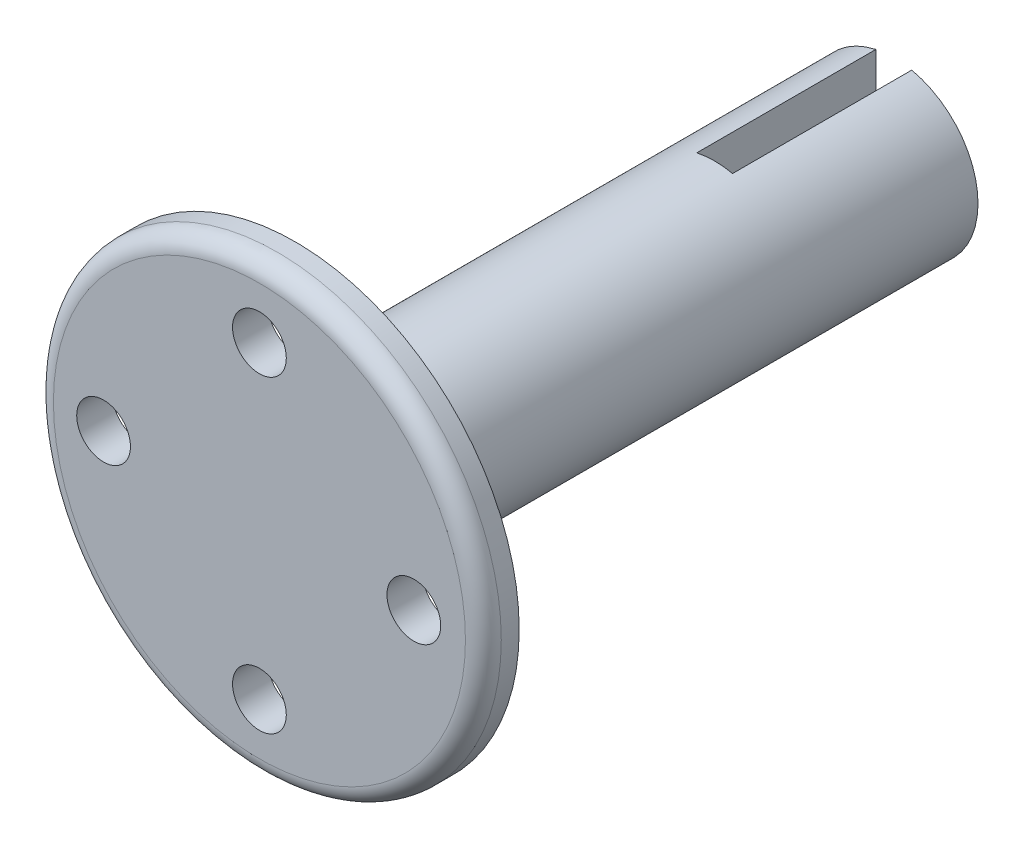
SolidWorks part; units mm, degrees
ref_plane "Alzado" through (0, 0, 0) normal (0, 0, 1) x (1, 0, 0)
ref_plane "Planta" through (0, 0, 0) normal (0, 1, 0) x (1, 0, 0)
ref_plane "Vista lateral" through (0, 0, 0) normal (1, 0, 0) x (0, 0, -1)
sketch "Croquis1" plane through (0, 0, 0) normal (0, 0, 1) x (1, 0, 0)
  circle A0 centre (0, 0) radius 12.5
  dimension "D1" = 25
extrude "Saliente-Extruir1" add sketch "Croquis1" along normal blind 2
fillet "Redondeo2" radius 1 1 edges at (12.5, 0, 2)
sketch "Croquis2" plane through (0, 0, 0) normal (0, 0, -1) x (-1, 0, 0)
  circle A0 centre (0, 0) radius 5
  dimension "D1" = 10
extrude "Saliente-Extruir2" add sketch "Croquis2" along normal blind 33.41
sketch "Croquis3" plane through (0, 0, 0) normal (0, 0, -1) x (-1, 0, 0)
  line L0 (0, 8.62) -> (0, -0.2266) construction
  line L1 (0, -0.2266) -> (0, -8.62) construction
  line L2 (8.7, 0) -> (0, 0) construction
  line L3 (0, 0) -> (-8.62, 0) construction
  circle A0 centre (0, 8.62) radius 1.5
  circle A1 centre (-8.62, 0) radius 1.5
  circle A2 centre (8.7, 0) radius 1.5
  circle A3 centre (0, -8.62) radius 1.5
  circle A4 centre (0, 0) radius 5 construction
  circle A5 centre (0, 0) radius 5 construction
  dimension "D1" = 3
  dimension "D2" = 3
  dimension "D3" = 3
  dimension "D4" = 3
  dimension "D5" = 2.12
  dimension "D6" = 2.12
  dimension "D7" = 2.12
  dimension "D8" = 2.2
extrude "Cortar-Extruir1" cut sketch "Croquis3" against normal blind 23.41
sketch "Croquis4" plane through (0, 0, -33.41) normal (0, 0, -1) x (-1, 0, 0)
  line L0 (-1, 4.899) -> (-1, 1.7321)
  line L1 (1, 4.899) -> (1, 1.7321)
  line L2 (1.5, 1.3229) -> (1.5, -1.3229)
  arc A0 (-1, 1.7321) -> (1.5, -1.3229) centre (0, 0) ccw
  circle A1 centre (0, 0) radius 5 construction
  circle A2 centre (0, 0) radius 5 construction
  arc A3 (1, 4.899) -> (-1, 4.899) centre (0, 0) ccw
  arc A4 (1.5, 1.3229) -> (1, 1.7321) centre (0, 0) ccw
  point P12 (1, 3.3155)
  dimension "D1" = 4
  dimension "D2" = 1
  dimension "D3" = 1
  dimension "D4" = 3.5
extrude "Cortar-Extruir2" cut sketch "Croquis4" against normal blind 10
sketch "Croquis5" plane through (0, 0, -33.41) normal (0, 0, -1) x (-1, 0, 0)
sketch "Croquis9" plane through (0, 0, -33.41) normal (0, 0, -1) x (-1, 0, 0)
  circle A0 centre (0, 0) radius 5
  circle A1 centre (0, 0) radius 4.7
  circle A2 centre (0, 0) radius 5 construction
  dimension "D1" = 0.3
extrude "Cortar-Extruir7" cut sketch "Croquis9" against normal up to surface (33.41 mm away) up to face at (-1.5, 8.62, 0)
